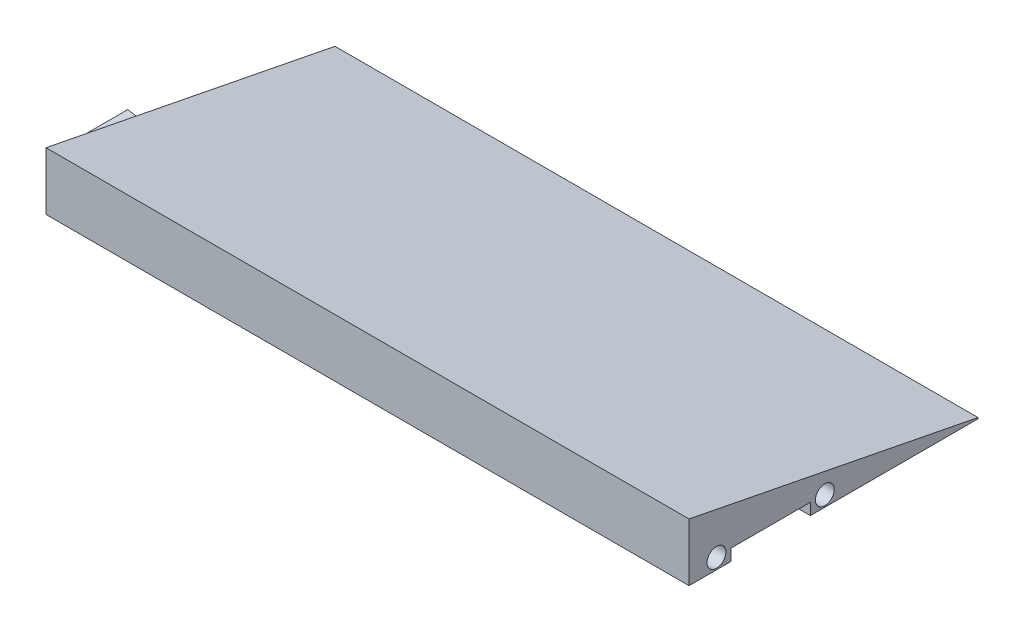
SolidWorks part; units mm, degrees
ref_plane "Front Plane" through (0, 0, 0) normal (0, 0, 1) x (1, 0, 0)
ref_plane "Top Plane" through (0, 0, 0) normal (0, 1, 0) x (1, 0, 0)
ref_plane "Right Plane" through (0, 0, 0) normal (1, 0, 0) x (0, 0, -1)
sketch "Sketch1" plane through (0, 0, 0) normal (1, 0, 0) x (0, 0, -1)
  line L0 (0, 0) -> (0, 20.32)
  line L1 (0, 20.32) -> (101.6, 0.4)
  line L2 (101.6, 0.4) -> (101.6, 0)
  line L3 (101.6, 0) -> (0, 0)
  dimension "D1" = 0.4
  dimension "D2" = 101.6
  dimension "D3" = 20.32
extrude "Boss-Extrude1" add sketch "Sketch1" along normal mid plane 391.16
sketch "Sketch2" plane through (195.58, 0, 0) normal (1, 0, 0) x (0, 0, -1)
  line L0 (0, 0) -> (101.6, 0) construction
  line L2 (0, 20.32) -> (0, 0) construction
  circle A0 centre (9.652, 3.81) radius 3.3147
  circle A1 centre (47.752, 3.81) radius 3.3147
  circle A3 centre (9.652, 3.81) radius 3.81 construction
  dimension "D1" = 38.1
  dimension "D2" = 6.6294
  dimension "D3" = 9.652
  dimension "D4" = 3.81
extrude "Cut-Extrude1" cut sketch "Sketch2" against normal blind 38.1
mirror "Mirror3" about plane through (0, 0, 0) normal (1, 0, 0) of "Cut-Extrude1"
sketch "Sketch3" plane through (-195.58, 0, 0) normal (-1, 0, 0) x (0, 0, 1)
  line L5 (0, 0) -> (-101.6, 0) construction
  line L6 (-42.672, 4.064) -> (-14.732, 4.064)
  line L7 (-42.672, 4.064) -> (-42.672, 0)
  line L8 (-42.672, 0) -> (-14.732, 0)
  line L9 (-14.732, 4.064) -> (-14.732, 0)
  line L10 (0, 20.32) -> (0, 0) construction
  dimension "D1" = 27.94
  dimension "D2" = 4.064
  dimension "D3" = 0
  dimension "D4" = 14.732
extrude "Cut-Extrude2" cut sketch "Sketch3" against normal through all
sketch "Sketch4" plane through (0, 0, 0) normal (0, -1, 0) x (1, 0, 0)
  line L1 (-141.0599, -42.672) -> (-142.3855, -52.1043)
  line L5 (-141.0599, -42.672) -> (-124.8644, -42.672)
  line L7 (-141.0599, -42.672) -> (-141.0599, -52.1043) construction
  line L11 (-124.8644, -42.672) -> (-123.5387, -52.1043)
  line L42 (-124.8644, -42.672) -> (-124.8644, -52.1043) construction
  line L43 (-195.58, -28.702) -> (195.58, -28.702) construction
  line L44 (-195.58, -14.732) -> (-195.58, -42.672) construction
  line L45 (-141.0599, -52.1043) -> (-124.8644, -52.1043)
  line L82 (-141.0599, -52.1043) -> (-142.3855, -52.1043)
  line L83 (195.58, -14.732) -> (195.58, -42.672) construction
  line L84 (-124.8644, -52.1043) -> (-123.5387, -52.1043)
  line L85 (-124.8644, -14.732) -> (-124.8644, -5.2997) construction
  line L86 (-73.8612, -42.672) -> (-75.1868, -52.1043)
  line L87 (-73.8612, -52.1043) -> (-75.1868, -52.1043)
  line L88 (-73.8612, -52.1043) -> (-57.6656, -52.1043)
  line L89 (-57.6656, -52.1043) -> (-56.34, -52.1043)
  line L90 (-57.6656, -42.672) -> (-56.34, -52.1043)
  line L91 (-73.8612, -42.672) -> (-57.6656, -42.672)
  line L92 (-10.7889, -42.672) -> (-12.1145, -52.1043)
  line L93 (-10.7889, -52.1043) -> (-12.1145, -52.1043)
  line L94 (-10.7889, -52.1043) -> (6.7323, -52.1043)
  line L97 (-10.7889, -42.672) -> (5.4067, -42.672)
  line L104 (123.2022, -42.672) -> (121.8766, -52.1043)
  line L105 (123.2022, -52.1043) -> (121.8766, -52.1043)
  line L106 (123.2022, -52.1043) -> (139.3978, -52.1043)
  line L107 (139.3978, -52.1043) -> (140.7234, -52.1043)
  line L108 (139.3978, -42.672) -> (140.7234, -52.1043)
  line L109 (123.2022, -42.672) -> (139.3978, -42.672)
  line L110 (-141.0599, -14.732) -> (-141.0599, -5.2997) construction
  line L111 (123.2022, -14.732) -> (139.3978, -14.732)
  line L112 (139.3978, -14.732) -> (140.7234, -5.2997)
  line L113 (139.3978, -5.2997) -> (140.7234, -5.2997)
  line L114 (123.2022, -5.2997) -> (139.3978, -5.2997)
  line L115 (123.2022, -5.2997) -> (121.8766, -5.2997)
  line L116 (123.2022, -14.732) -> (121.8766, -5.2997)
  line L123 (-10.7889, -14.732) -> (5.4067, -14.732)
  line L124 (5.4067, -14.732) -> (6.7323, -5.2997)
  line L126 (-10.7889, -5.2997) -> (6.7323, -5.2997)
  line L127 (-10.7889, -5.2997) -> (-12.1145, -5.2997)
  line L128 (-10.7889, -14.732) -> (-12.1145, -5.2997)
  line L129 (-73.8612, -14.732) -> (-57.6656, -14.732)
  line L130 (-57.6656, -14.732) -> (-56.34, -5.2997)
  line L131 (-57.6656, -5.2997) -> (-56.34, -5.2997)
  line L132 (-73.8612, -5.2997) -> (-57.6656, -5.2997)
  line L133 (-73.8612, -5.2997) -> (-75.1868, -5.2997)
  line L134 (-73.8612, -14.732) -> (-75.1868, -5.2997)
  line L135 (-124.8644, -5.2997) -> (-123.5387, -5.2997)
  line L136 (-141.0599, -5.2997) -> (-142.3855, -5.2997)
  line L137 (-141.0599, -5.2997) -> (-124.8644, -5.2997)
  line L138 (-124.8644, -14.732) -> (-123.5387, -5.2997)
  line L139 (-141.0599, -14.732) -> (-124.8644, -14.732)
  line L140 (-141.0599, -14.732) -> (-142.3855, -5.2997)
  line L141 (-10.7889, -42.672) -> (-10.7889, -52.1043) construction
  line L142 (-141.0599, -42.672) -> (-141.0599, -52.1043) construction
  line L143 (195.58, -42.672) -> (-195.58, -42.672) construction
  line L144 (195.58, -42.672) -> (-195.58, -42.672) construction
  line L145 (-73.8612, -42.672) -> (-73.8612, -52.1043) construction
  line L146 (-57.6656, -52.1043) -> (-57.6656, -42.672)
  line L147 (5.4067, -42.672) -> (5.4067, -52.1043) construction
  line L148 (6.7323, -52.1043) -> (5.4067, -42.672)
  line L150 (56.2067, -42.672) -> (54.881, -52.1043)
  line L151 (56.2067, -52.1043) -> (54.881, -52.1043)
  line L152 (56.2067, -52.1043) -> (73.7278, -52.1043)
  line L153 (56.2067, -42.672) -> (72.4022, -42.672)
  line L154 (56.2067, -42.672) -> (56.2067, -52.1043) construction
  line L155 (72.4022, -42.672) -> (72.4022, -52.1043) construction
  line L156 (73.7278, -52.1043) -> (72.4022, -42.672)
  line L157 (56.2067, -14.732) -> (72.4022, -14.732)
  line L158 (73.7278, -5.2997) -> (72.4022, -14.732)
  line L159 (56.2067, -5.2997) -> (73.7278, -5.2997)
  line L160 (56.2067, -5.2997) -> (54.881, -5.2997)
  line L161 (56.2067, -14.732) -> (54.881, -5.2997)
  line L162 (123.2022, -42.672) -> (123.2022, -52.1043) construction
  line L163 (139.3978, -52.1043) -> (139.3978, -42.672) construction
  line L164 (123.2022, -14.732) -> (123.2022, -5.2997)
  line L165 (139.3978, -5.2997) -> (139.3978, -14.732)
  line M49 (195.58, -42.672) -> (-195.58, -42.672)
  dimension "D1" = 9.525
  dimension "D2" = 8
  dimension "D3" = 54.5201
  dimension "D4" = 0
  dimension "D5" = 0
  dimension "D7" = 0
  dimension "D8" = 18.8468
  dimension "D9" = 8
  dimension "D10" = 51.0032
  dimension "D6" = 8
  dimension "D11" = 46.8767
  dimension "D12" = 18.8468
  dimension "D13" = 8
  dimension "D14" = 8
  dimension "D15" = 8
  dimension "D16" = 18.8468
  dimension "D17" = 16.1956
  dimension "D18" = 8
  dimension "D19" = 8
  dimension "D20" = 18.8468
  dimension "D21" = 50.8
  dimension "D22" = 50.8
  dimension "D23" = 8
  dimension "D24" = 8
  dimension "D25" = 0
extrude "Cut-Extrude3" cut sketch "Sketch4" against normal blind 4.064 contours L94 L148 L92 L93 M49 | L152 L156 L153 L150 L151 | L161 L157 L158 L159 L160 | L165 L114 L164 L111 | L128 L123 L124 L126 L127 | L108 L104 L105 L106 L107 M49 | L116 L164 L115 | L113 L165 L112 | L132 L131 L130 L129 L134 L133 | L137 L135 L138 L139 L140 L136 | L5 L11 L84 L45 L82 L1 | L91 L86 L87 L88
sketch "Sketch5" plane through (-195.58, 0, 0) normal (-1, 0, 0) x (0, 0, 1)
  line L1 (-101.6, 0) -> (0, 0)
  line L2 (-101.6, 0) -> (-101.6, 20.32)
  line L3 (-101.6, 20.32) -> (0, 20.32)
  line L4 (0, 0) -> (0, 20.32)
extrude "Cut-Extrude4" cut sketch "Sketch5" against normal blind 165.1
sketch "Sketch6" plane through (0, 4.064, 0) normal (0, -1, 0) x (1, 0, 0)
  line L0 (-30.48, -20.447) -> (-30.48, -36.8458)
  line L1 (-30.48, -14.732) -> (-30.48, -42.672) construction
  line L2 (-30.48, -36.8458) -> (-39.9123, -38.1714)
  line L3 (-39.9123, -38.1714) -> (-39.9123, -19.1214)
  line L4 (-39.9123, -19.1214) -> (-30.48, -20.447)
  line L5 (-30.48, -20.447) -> (-39.9123, -20.447) construction
  line L6 (-30.48, -36.8458) -> (-39.9123, -36.8458) construction
  line L7 (-10.7889, -14.732) -> (-30.48, -14.732) construction
  dimension "D1" = 8
  dimension "D2" = 8
  dimension "D3" = 19.05
  dimension "D4" = 9.525
  dimension "D5" = 5.715
extrude "Boss-Extrude2" add sketch "Sketch6" against normal blind 4.064
sketch "Sketch7" plane through (-30.48, 0, 0) normal (-1, 0, 0) x (0, 0, 1)
  line L0 (0, 0) -> (0, 20.32) construction
  line L1 (-14.732, 4.064) -> (-20.447, 4.064) construction
  line L2 (-36.8458, 4.064) -> (-42.672, 4.064) construction
  circle A0 centre (-15.24, 8.128) radius 1.905
  circle A1 centre (-45.72, 8.128) radius 1.905
  dimension "D4" = 3.81
  dimension "D5" = 3.81
  dimension "D1" = 15.24
  dimension "D2" = 30.48
  dimension "D3" = 4.064
  dimension "D6" = 4.064
extrude "Cut-Extrude5" cut sketch "Sketch7" against normal blind 12.7
